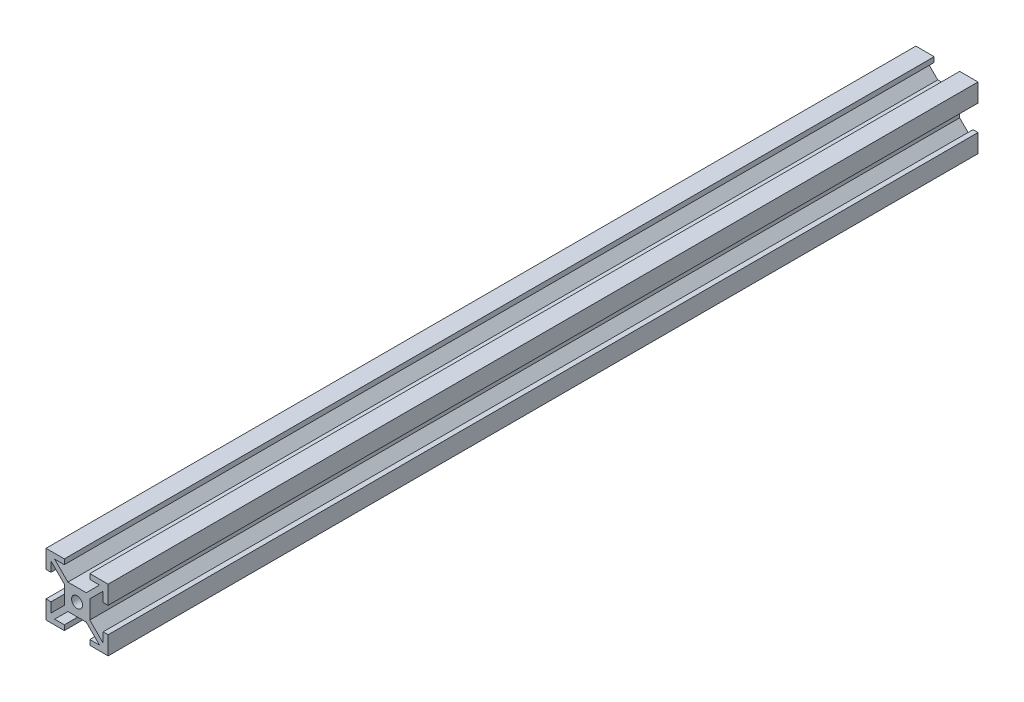
SolidWorks part; units mm, degrees
ref_plane "Front Plane" through (0, 0, 0) normal (0, 0, 1) x (1, 0, 0)
ref_plane "Top Plane" through (0, 0, 0) normal (0, 1, 0) x (1, 0, 0)
ref_plane "Right Plane" through (0, 0, 0) normal (1, 0, 0) x (0, 0, -1)
sketch "Sketch1" plane through (0, 0, 0) normal (0, 0, 1) x (1, 0, 0)
  line L0 (-8.38, 4.1) -> (-10, 4.1)
  line L1 (-2.9545, 4.1) -> (2.9545, 4.1)
  line L2 (-4.1, 2.9545) -> (-4.1, -2.9545)
  line L3 (-2.9545, -4.1) -> (2.9545, -4.1)
  line L4 (4.1, 2.9545) -> (4.1, -2.9545)
  line L5 (-4.1, 4.1) -> (4.1, -4.1) construction
  line L6 (-4.1, -4.1) -> (4.1, 4.1) construction
  line L7 (-10, 10) -> (-4.1, 10)
  line L8 (-10, 10) -> (-10, 4.1)
  line L9 (-10, -10) -> (-4.1, -10)
  line L10 (10, 10) -> (10, 4.1)
  line L11 (-10, 10) -> (10, -10) construction
  line L12 (-10, -10) -> (10, 10) construction
  line L13 (-7.2345, 8.38) -> (-4.1, 8.38)
  line L14 (-8.38, 7.2345) -> (-8.38, 4.1)
  line L15 (-7.2345, -8.38) -> (-4.1, -8.38)
  line L16 (8.38, 7.2345) -> (8.38, 4.1)
  line L17 (-8.38, 8.38) -> (8.38, -8.38) construction
  line L18 (-8.38, -8.38) -> (8.38, 8.38) construction
  line L19 (-4.1, 8.38) -> (-4.1, 10)
  line L20 (4.1, 10) -> (4.1, 8.38)
  line L21 (8.38, 4.1) -> (10, 4.1)
  line L22 (-8.38, -4.1) -> (-10, -4.1)
  line L23 (-4.1, -8.38) -> (-4.1, -10)
  line L24 (8.38, -4.1) -> (10, -4.1)
  line L25 (4.1, -8.38) -> (4.1, -10)
  line L26 (-5.464, 5.464) -> (-4.8912, 6.0368) construction
  line L27 (-4.1, 2.9545) -> (-8.38, 7.2345)
  line L28 (-2.9545, 4.1) -> (-7.2345, 8.38)
  line L29 (0, 11.3108) -> (0, -17.1823) construction
  line L30 (-16.7028, 0) -> (14.4032, 0) construction
  line L31 (-2.9545, -4.1) -> (-7.2345, -8.38)
  line L32 (-4.1, -2.9545) -> (-8.38, -7.2345)
  line L33 (2.9545, -4.1) -> (7.2345, -8.38)
  line L34 (4.1, -2.9545) -> (8.38, -7.2345)
  line L35 (4.1, 2.9545) -> (8.38, 7.2345)
  line L36 (2.9545, 4.1) -> (7.2345, 8.38)
  line L37 (4.1, 8.38) -> (7.2345, 8.38)
  line L38 (4.1, 10) -> (10, 10)
  line L39 (-8.38, -4.1) -> (-8.38, -7.2345)
  line L40 (-10, -4.1) -> (-10, -10)
  line L41 (8.38, -4.1) -> (8.38, -7.2345)
  line L42 (10, -4.1) -> (10, -10)
  line L43 (4.1, -8.38) -> (7.2345, -8.38)
  line L44 (4.1, -10) -> (10, -10)
  circle A0 centre (0, 0) radius 1.77
  point P0 (0, 0)
  point P6 (0, 0)
  dimension "D5" = 3.54
  dimension "D1" = 8.2
  dimension "D2" = 20
  dimension "D3" = 8.2
  dimension "D4" = 20
  dimension "D6" = 16.76
  dimension "D7" = 16.76
  dimension "D8" = 0.81
  dimension "D9" = 135
  dimension "D10" = 7.7696
  dimension "D11" = 5.0536
extrude "Boss-Extrude1" add sketch "Sketch1" along normal blind 280
